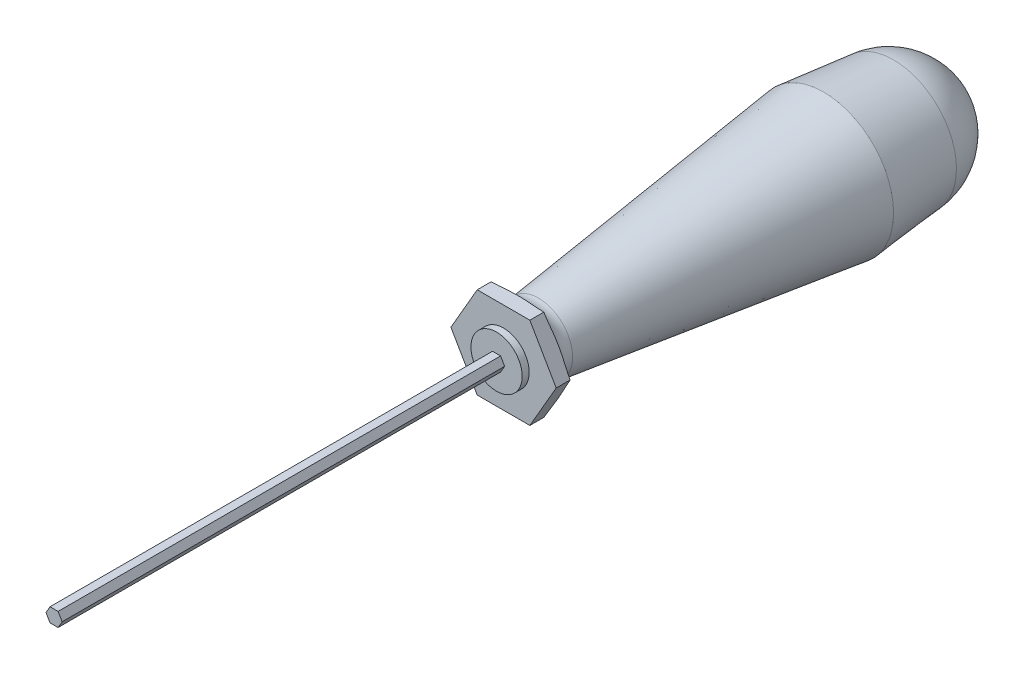
SolidWorks part; units mm, degrees
ref_plane "Alzado" through (0, 0, 0) normal (0, 0, 1) x (1, 0, 0)
ref_plane "Planta" through (0, 0, 0) normal (0, 1, 0) x (1, 0, 0)
ref_plane "Vista lateral" through (0, 0, 0) normal (1, 0, 0) x (0, 0, -1)
sketch "Croquis1" plane through (0, 0, 0) normal (0, 0, 1) x (1, 0, 0)
  line L1 (1.7321, 0) -> (0.866, 1.5)
  line L2 (0.866, 1.5) -> (-0.866, 1.5)
  line L3 (-0.866, 1.5) -> (-1.7321, 0)
  line L4 (-1.7321, 0) -> (-0.866, -1.5)
  line L5 (-0.866, -1.5) -> (0.866, -1.5)
  line L6 (0.866, -1.5) -> (1.7321, 0)
  circle A0 centre (0, 0) radius 1.5 construction
  point P1 (0, 0)
  dimension "D1" = 3
extrude "Saliente-Extruir1" add sketch "Croquis1" against normal blind 120
sketch "Croquis2" plane through (0, 0, 0) normal (1, 0, 0) x (0, 0, -1)
  line L0 (0, 0) -> (210.6413, 0) construction
  line L1 (95, 0) -> (95, 5.5)
  line L2 (95, 5.5) -> (96.5, 5.5)
  line L3 (96.5, 5.5) -> (96.5, 11.3024)
  line L4 (96.5, 11.3024) -> (99.5, 11.3024)
  line L5 (103.9969, 7.3334) -> (165.2382, 15)
  line L6 (165.2382, 15) -> (180.2382, 13.5)
  line L7 (193.2382, 0) -> (95, 0)
  line L8 (193.2382, 0) -> (193.2382, 44.0359) construction
  arc A0 (99.5, 11.3024) -> (103.9969, 7.3334) centre (103.5, 11.3024) ccw
  arc A1 (180.2382, 13.5) -> (193.2382, 0) centre (178.7986, -0.8955) cw
  point P14 (171.5034, 15)
  point P16 (200.5561, 0)
  point P18 (0, 0)
  point P19 (0, 0)
  point P20 (0, 0)
  dimension "D6" = 4
  dimension "D9" = 13.5
  dimension "D1" = 98.2382
  dimension "D2" = 3
  dimension "D3" = 1.5
  dimension "D4" = 15
  dimension "D5" = 28
  dimension "D7" = 5.5
  dimension "D8" = 11.3024
  dimension "D10" = 15
  dimension "D11" = 25
revolve "Revolución1" add sketch "Croquis2" angle 360 about L0
sketch "Croquis4" plane through (0, 0, -96.5) normal (0, 0, 1) x (1, 0, 0)
  line L1 (11.3024, 0) -> (5.6512, 9.7882)
  line L2 (5.6512, 9.7882) -> (-5.6512, 9.7882)
  line L3 (-5.6512, 9.7882) -> (-11.3024, 0)
  line L4 (-11.3024, 0) -> (-5.6512, -9.7882)
  line L5 (-5.6512, -9.7882) -> (5.6512, -9.7882)
  line L6 (5.6512, -9.7882) -> (11.3024, 0)
  circle A0 centre (0, 0) radius 9.7882 construction
  circle A2 centre (0, 0) radius 11.3024 construction
extrude "Cortar-Extruir4" cut sketch "Croquis4" against normal blind 4 flip side to cut
